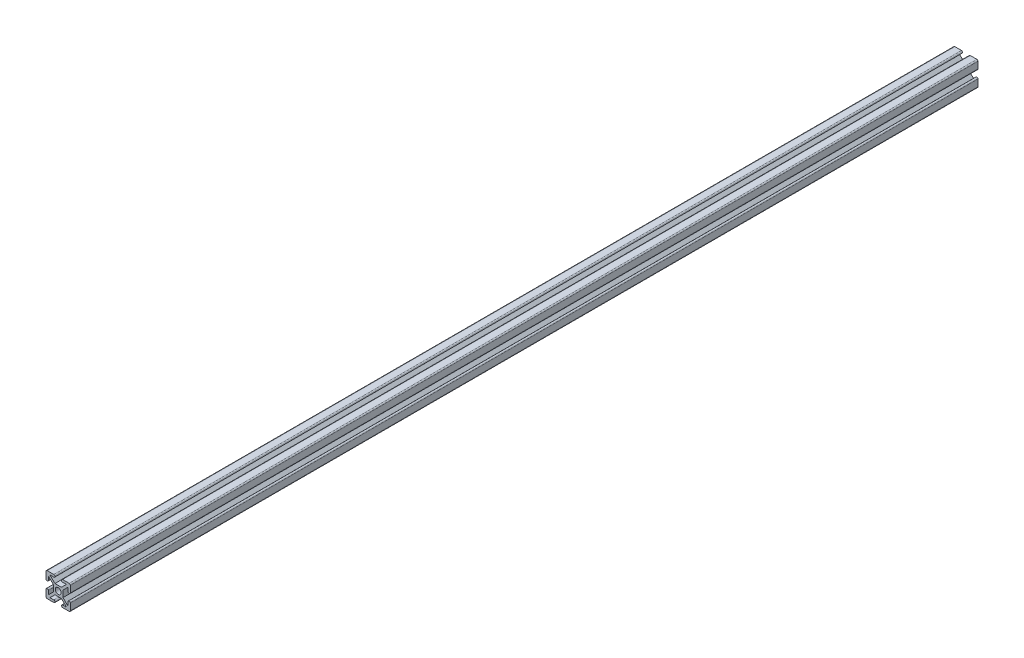
SolidWorks part; units mm, degrees
ref_plane "Alzado" through (0, 0, 0) normal (0, 0, 1) x (1, 0, 0)
ref_plane "Planta" through (0, 0, 0) normal (0, 1, 0) x (1, 0, 0)
ref_plane "Vista lateral" through (0, 0, 0) normal (1, 0, 0) x (0, 0, -1)
sketch "Croquis1" plane through (0, 0, 0) normal (0, 0, 1) x (1, 0, 0)
  line L0 (-42.257, 14.1582) -> (-42.257, 15.5832) construction
  line L1 (-23.2041, -1.9918) -> (-18.4791, -1.9918)
  line L2 (-43.682, 23.7332) -> (-43.682, 15.5832)
  line L3 (-42.257, 25.1582) -> (-34.107, 25.1582)
  line L4 (-23.257, 25.1582) -> (-15.107, 25.1582)
  line L5 (-38.7791, -1.9918) -> (-34.0541, -1.9918)
  line L6 (-34.682, 14.1582) -> (-34.682, 6.1582)
  line L7 (-43.6291, 4.7332) -> (-43.6291, -3.4168)
  line L8 (-42.2305, -4.8153) -> (-34.0541, -4.8418)
  line L9 (-13.682, 23.7332) -> (-13.682, 15.6869)
  line L10 (-40.832, 20.3082) -> (-40.832, 15.5832)
  line L11 (-13.682, 4.8369) -> (-13.682, -3.4168)
  line L12 (-32.682, 23.7332) -> (-34.107, 23.7332) construction
  line L13 (-23.2041, -4.8418) -> (-15.107, -4.8418)
  line L14 (-38.832, 22.3082) -> (-34.107, 22.3082)
  line L15 (-40.832, 4.7332) -> (-40.832, 0.0082)
  line L16 (-24.682, 23.7332) -> (-23.257, 23.7332) construction
  line L17 (-23.257, 22.3082) -> (-18.532, 22.3082)
  line L18 (-15.107, 14.2619) -> (-15.107, 15.6869) construction
  line L19 (-32.682, 16.1582) -> (-38.832, 22.3082)
  line L20 (-16.532, 20.3082) -> (-16.532, 15.6869)
  line L21 (-15.107, 6.2619) -> (-15.107, 4.8369) construction
  line L22 (-34.682, 14.1582) -> (-40.832, 20.3082)
  line L23 (-16.532, 4.8369) -> (-16.532, 0.0082)
  line L24 (-24.6291, -3.4168) -> (-23.2041, -3.4168) construction
  line L25 (-34.682, 6.1582) -> (-40.832, 0.0082)
  line L26 (-32.682, 16.1582) -> (-24.682, 16.1582)
  line L27 (-24.682, 16.1582) -> (-18.532, 22.3082)
  line L28 (-42.2305, 6.1582) -> (-42.2305, 4.7332) construction
  line L29 (-38.7791, -1.9918) -> (-32.6291, 4.1582)
  line L30 (-32.6291, 4.1582) -> (-24.6291, 4.1582)
  line L31 (-24.6291, 4.1582) -> (-18.4791, -1.9918)
  line L32 (-32.6291, -3.4168) -> (-34.0541, -3.4168) construction
  line L33 (-22.682, 6.1582) -> (-16.532, 0.0082)
  line L34 (-22.682, 14.1582) -> (-16.532, 20.3082)
  line L35 (-22.682, 14.1582) -> (-22.682, 6.1582)
  circle A0 centre (-28.6291, 10.1582) radius 3.645
  arc A1 (-43.682, 15.5832) -> (-40.832, 15.5832) centre (-42.257, 15.5832) ccw
  arc A2 (-34.107, 22.3082) -> (-34.107, 25.1582) centre (-34.107, 23.7332) ccw
  arc A3 (-23.257, 25.1582) -> (-23.257, 22.3082) centre (-23.257, 23.7332) ccw
  arc A4 (-16.532, 15.6869) -> (-13.682, 15.6869) centre (-15.107, 15.6869) ccw
  arc A5 (-13.682, 4.8369) -> (-16.532, 4.8369) centre (-15.107, 4.8369) ccw
  arc A6 (-23.2041, -1.9918) -> (-23.2041, -4.8418) centre (-23.2041, -3.4168) ccw
  arc A7 (-40.832, 4.7332) -> (-43.6291, 4.7332) centre (-42.2305, 4.7332) ccw
  arc A8 (-34.0541, -4.8418) -> (-34.0541, -1.9918) centre (-34.0541, -3.4168) ccw
  arc A9 (-43.6291, -3.4168) -> (-42.2305, -4.8153) centre (-42.2305, -3.4168) ccw
  arc A10 (-15.107, -4.8418) -> (-13.682, -3.4168) centre (-15.107, -3.4168) ccw
  arc A11 (-13.682, 23.7332) -> (-15.107, 25.1582) centre (-15.107, 23.7332) ccw
  arc A12 (-42.257, 25.1582) -> (-43.682, 23.7332) centre (-42.257, 23.7332) ccw
  dimension "D1" = 1.425
  dimension "D2" = 1.425
  dimension "D3" = 1.425
  dimension "D4" = 1.425
  dimension "D5" = 1.425
  dimension "D6" = 1.425
  dimension "D7" = 1.425
  dimension "D8" = 1.425
extrude "Saliente-Extruir1" add sketch "Croquis1" along normal blind 1119.12
